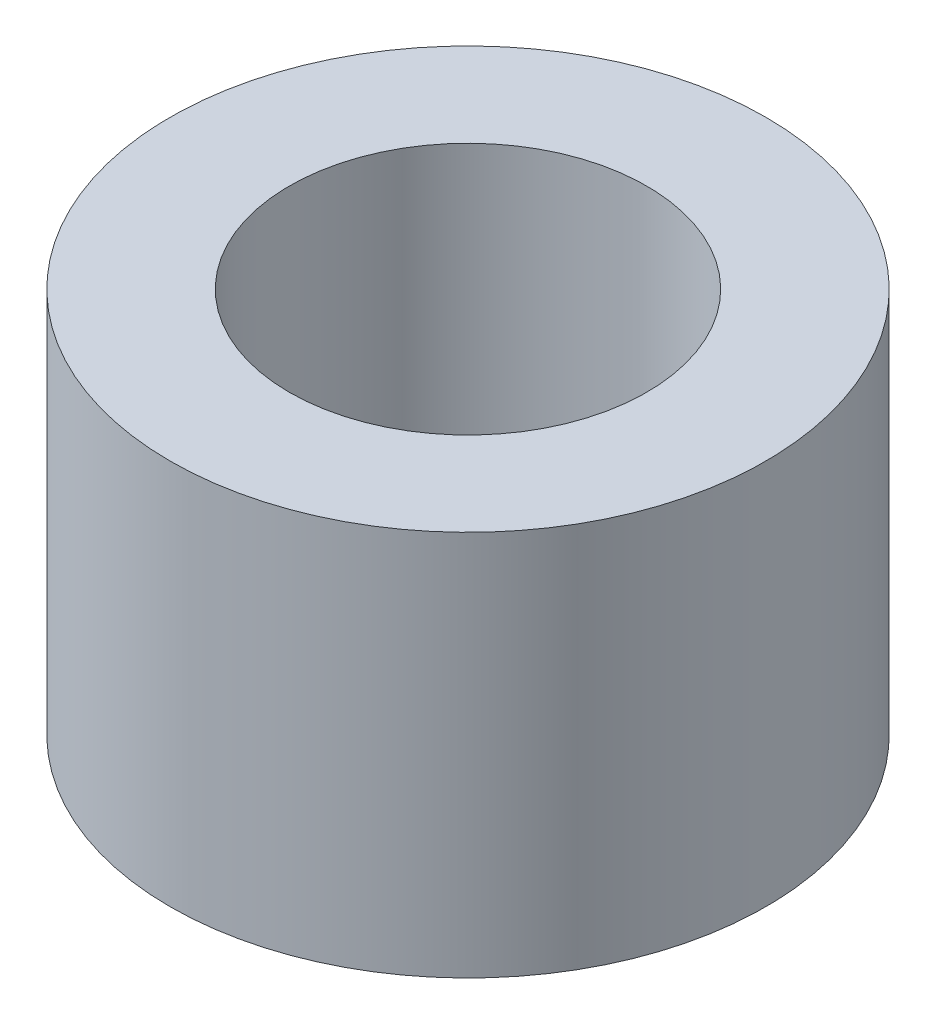
SolidWorks part; units mm, degrees
ref_plane "Front Plane" through (0, 0, 0) normal (0, 0, 1) x (1, 0, 0)
ref_plane "Top Plane" through (0, 0, 0) normal (0, 1, 0) x (1, 0, 0)
ref_plane "Right Plane" through (0, 0, 0) normal (1, 0, 0) x (0, 0, -1)
sketch "Sketch1" plane through (0, 0, 0) normal (0, 1, 0) x (1, 0, 0)
  circle A0 centre (0, 0) radius 9.525
  circle A1 centre (0, 0) radius 15.875
  dimension "D1" = 19.05
  dimension "D2" = 31.75
extrude "Boss-Extrude1" add sketch "Sketch1" along normal mid plane 20.574
